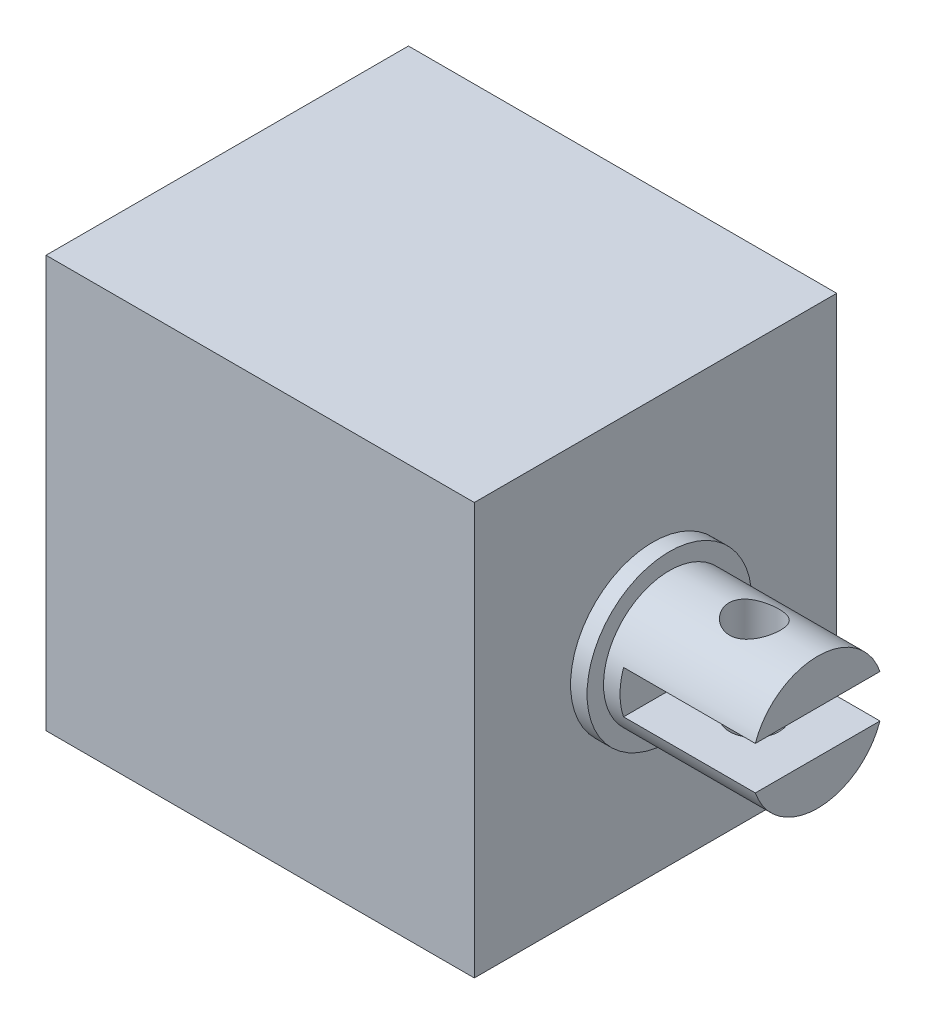
SolidWorks part; units mm, degrees
ref_plane "Front Plane" through (0, 0, 0) normal (0, 0, 1) x (1, 0, 0)
ref_plane "Top Plane" through (0, 0, 0) normal (0, 1, 0) x (1, 0, 0)
ref_plane "Right Plane" through (0, 0, 0) normal (1, 0, 0) x (0, 0, -1)
sketch "Sketch3" plane through (0, 0, 0) normal (0, 0, 1) x (1, 0, 0)
  line L1 (13, -12.5) -> (-13, -12.5)
  line L2 (13, -12.5) -> (13, 12.5)
  line L3 (13, 12.5) -> (-13, 12.5)
  line L4 (-13, -12.5) -> (-13, 12.5)
  line L5 (13, -12.5) -> (-13, 12.5) construction
  line L6 (13, 12.5) -> (-13, -12.5) construction
  point P0 (0, 0)
  dimension "D1" = 26
  dimension "D2" = 25
extrude "Boss-Extrude2" add sketch "Sketch3" along normal blind 22
sketch "Sketch4" plane through (13, 0, 0) normal (1, 0, 0) x (0, 0, -1)
  circle A0 centre (-11.1565, 0) radius 5
  dimension "D1" = 10
extrude "Boss-Extrude3" add sketch "Sketch4" along normal blind 1
sketch "Sketch5" plane through (14, 0, 0) normal (1, 0, 0) x (0, 0, -1)
  circle A1 centre (-11.1565, 0) radius 4
  circle A3 centre (-11.1565, 0) radius 5 construction
  point P1 (0, 0)
  dimension "D1" = 8
extrude "Boss-Extrude4" add sketch "Sketch5" along normal blind 9
ref_plane "Plane1" through (0, 0, 11) normal (0, 0, 1) x (1, 0, 0)
sketch "Sketch7" plane through (0, 0, 11) normal (0, 0, 1) x (1, 0, 0)
  line L0 (23, -4) -> (23, 4) construction
  line L1 (23, 1.3) -> (15, 1.3)
  line L2 (23, 1.3) -> (23, -1.3)
  line L3 (23, -1.3) -> (15, -1.3)
  line L4 (15, 1.3) -> (15, -1.3)
  line L5 (13, 12.5) -> (-13, 12.5) construction
  point P6 (15, 0)
  dimension "D1" = 2.6
  dimension "D2" = 12.5
  dimension "D3" = 8
extrude "Cut-Extrude1" cut sketch "Sketch7" against normal blind 5
mirror "Mirror1" about plane through (0, 0, 11) normal (0, 0, 1) of "Cut-Extrude1"
sketch "Sketch8" plane through (0, 0, 0) normal (0, 1, 0) x (1, 0, 0)
  line L0 (-13.75, -11) -> (13.75, -11) construction
  line L1 (23, -14.9394) -> (23, -7.3737) construction
  circle A0 centre (19, -11) radius 1.5
  dimension "D2" = 3
  dimension "D1" = 4
extrude "Cut-Extrude2" cut sketch "Sketch8" against normal blind 6
mirror "Mirror2" about plane through (0, 0, 0) normal (0, 1, 0) of "Cut-Extrude2"
